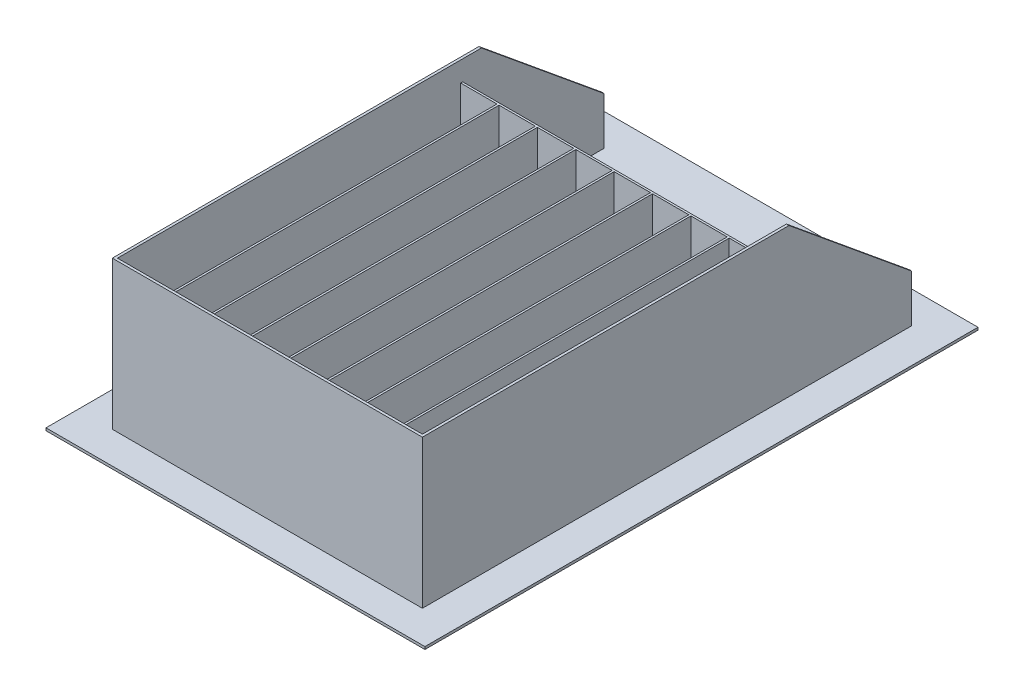
SolidWorks part; units mm, degrees
material "6061-T6 (SS)"
ref_plane "Front Plane" through (0, 0, 0) normal (0, 0, 1) x (1, 0, 0)
ref_plane "Top Plane" through (0, 0, 0) normal (0, 1, 0) x (1, 0, 0)
ref_plane "Right Plane" through (0, 0, 0) normal (1, 0, 0) x (0, 0, -1)
sketch "Sketch1" plane through (0, 0, 0) normal (0, 1, 0) x (1, 0, 0)
  line L1 (0, 0) -> (45.6, 0)
  line L2 (0, 0) -> (0, 430.25)
  line L3 (0, 430.25) -> (45.6, 430.25)
  line L4 (382.3, 0) -> (382.3, 430.25)
  line L5 (385.5, -3.2) -> (385.5, 432.75)
  line L6 (-3.2, -3.2) -> (385.5, -3.2)
  line L7 (-3.2, -3.2) -> (-3.2, 432.75)
  line L8 (-3.2, 433.45) -> (385.5, 433.45) construction
  line L9 (-3.2, 432.75) -> (385.5, 432.75)
  line L10 (45.6, 430.25) -> (45.6, 0)
  line L11 (-3.2, -3.2) -> (-3.2, 433.45) construction
  line L12 (385.5, -3.2) -> (385.5, 433.45) construction
  line L13 (48.1, 0) -> (48.1, 430.25)
  line L14 (48.1, 430.25) -> (93.7, 430.25)
  line L15 (48.1, 0) -> (93.7, 0)
  line L16 (0, 430.25) -> (382.3, 430.25) construction
  line L17 (93.7, 430.25) -> (93.7, 0)
  line L18 (0, 0) -> (382.3, 0) construction
  line L19 (96.2, 0) -> (96.2, 430.25)
  line L20 (141.8, 430.25) -> (141.8, 0)
  line L21 (144.3, 0) -> (144.3, 430.25)
  line L22 (189.9, 430.25) -> (189.9, 0)
  line L23 (192.4, 0) -> (192.4, 430.25)
  line L24 (238, 430.25) -> (238, 0)
  line L25 (240.5, 0) -> (240.5, 430.25)
  line L26 (286.1, 430.25) -> (286.1, 0)
  line L27 (288.6, 0) -> (288.6, 430.25)
  line L28 (334.2, 430.25) -> (334.2, 0)
  line L29 (336.7, 0) -> (336.7, 430.25)
  line L30 (96.2, 430.25) -> (141.8, 430.25)
  line L31 (144.3, 430.25) -> (189.9, 430.25)
  line L32 (96.2, 0) -> (141.8, 0)
  line L33 (144.3, 0) -> (189.9, 0)
  line L34 (192.4, 0) -> (238, 0)
  line L35 (240.5, 0) -> (286.1, 0)
  line L36 (288.6, 0) -> (334.2, 0)
  line L37 (336.7, 0) -> (382.3, 0)
  line L38 (192.4, 430.25) -> (238, 430.25)
  line L39 (240.5, 430.25) -> (286.1, 430.25)
  line L40 (288.6, 430.25) -> (334.2, 430.25)
  line L41 (336.7, 430.25) -> (382.3, 430.25)
  dimension "D1" = 430.25
  dimension "D2" = 382.3
  dimension "D4" = 2.5
  dimension "D3" = 3.2
  dimension "D5" = 2.5
  dimension "D6" = 45.6
  dimension "D8" = 45.6
  dimension "D7" = 7
extrude "Boss-Extrude1" add sketch "Sketch1" along normal blind 189
sketch "Sketch2" plane through (0, 0, 3.2) normal (0, 0, 1) x (1, 0, 0)
  line L0 (385.5, 189) -> (385.5, 0) construction
  line L1 (-3.2, 0) -> (385.5, 0)
  line L2 (-3.2, 0) -> (-3.2, 3.2)
  line L3 (-3.2, 3.2) -> (385.5, 3.2)
  line L4 (385.5, 0) -> (385.5, 3.2)
  dimension "D1" = 3.2
extrude "Boss-Extrude2" add sketch "Sketch2" against normal through all
sketch "Sketch3" plane through (0, 189, 0) normal (0, 1, 0) x (1, 0, 0)
  line L0 (0, 430.25) -> (0, 432.75)
  line L1 (385.5, 432.75) -> (-3.2, 432.75) construction
  line L2 (0, 432.75) -> (382.3, 432.75)
  line L3 (382.3, 430.25) -> (382.3, 432.75)
  line L4 (382.3, 430.25) -> (336.7, 430.25)
  line L5 (336.7, 430.25) -> (336.7, 0)
  line L6 (336.7, 0) -> (334.2, 0)
  line L7 (334.2, 0) -> (334.2, 430.25) construction
  line L8 (334.2, 0) -> (334.2, 430.25) construction
  line L9 (334.2, 0) -> (334.2, 430.25)
  line L10 (334.2, 430.25) -> (288.6, 430.25)
  line L11 (288.6, 430.25) -> (288.6, 0)
  line L12 (288.6, 0) -> (286.1, 0)
  line L13 (286.1, 0) -> (286.1, 430.25)
  line L14 (286.1, 430.25) -> (240.5, 430.25)
  line L15 (240.5, 430.25) -> (240.5, 0)
  line L16 (240.5, 0) -> (238, 0)
  line L17 (238, 0) -> (238, 430.25)
  line L18 (238, 430.25) -> (192.4, 430.25)
  line L19 (192.4, 430.25) -> (192.4, 0)
  line L20 (192.4, 0) -> (189.9, 0)
  line L21 (189.9, 0) -> (189.9, 430.25)
  line L22 (189.9, 430.25) -> (144.3, 430.25)
  line L23 (144.3, 430.25) -> (144.3, 0)
  line L24 (144.3, 0) -> (141.8, 0)
  line L25 (141.8, 0) -> (141.8, 430.25)
  line L26 (141.8, 430.25) -> (96.2, 430.25)
  line L27 (96.2, 430.25) -> (96.2, 0)
  line L28 (96.2, 0) -> (93.7, 0)
  line L29 (93.7, 0) -> (93.7, 430.25)
  line L30 (93.7, 430.25) -> (48.1, 430.25)
  line L31 (48.1, 430.25) -> (48.1, 0)
  line L32 (48.1, 0) -> (45.6, 0)
  line L33 (45.6, 0) -> (45.6, 430.25)
  line L34 (45.6, 430.25) -> (0, 430.25)
extrude "Cut-Extrude1" cut sketch "Sketch3" against normal blind 25
sketch "Sketch4" plane through (385.5, 0, 0) normal (1, 0, 0) x (0, 0, -1)
  line L0 (432.75, 189) -> (662.75, 0)
  line L1 (432.75, 0) -> (662.75, 0)
  line L2 (432.75, 0) -> (432.75, 189)
  dimension "D1" = 230
extrude "Boss-Extrude4" add sketch "Sketch4" against normal blind 3.2 contours L0 L1 L2
sketch "Sketch7" plane through (-3.2, 0, 0) normal (-1, 0, 0) x (0, 0, 1)
  line L0 (-432.75, 164) -> (-432.75, 189)
  line L8 (-430.25, 3.2) -> (0, 3.2)
  line L9 (0, 3.2) -> (0, 189)
  line L10 (0, 189) -> (-432.75, 189)
  line L11 (-432.75, 189) -> (-662.75, 0)
  line L12 (-662.75, 0) -> (-432.75, 0)
  line L13 (-432.75, 0) -> (-432.75, 164)
  line L14 (-432.75, 164) -> (-430.25, 164)
  line L15 (-430.25, 164) -> (-430.25, 3.2)
  line L19 (-432.75, 189) -> (-662.75, 0)
  line L20 (-662.75, 0) -> (-432.75, 0)
  line L21 (-432.75, 0) -> (-432.75, 164)
  dimension "D1" = 0
extrude "Boss-Extrude5" add sketch "Sketch7" against normal blind 3.2
sketch "Sketch9" plane through (0, 0, 0) normal (1, 0, 0) x (0, 0, -1)
  line L0 (662.75, 0) -> (658.8558, 3.2)
  line L1 (432.75, 0) -> (662.75, 0)
  line L2 (432.75, 0) -> (432.75, 3.2)
  line L3 (432.75, 3.2) -> (658.8558, 3.2)
  line L5 (432.75, 189) -> (662.75, 0) construction
  line L6 (662.75, 0) -> (432.75, 0) construction
  point P2 (652.75, 0)
  dimension "D1" = 3.2
extrude "Boss-Extrude6" add sketch "Sketch9" along normal up to next
sketch "Sketch11" plane through (385.5, 0, 0) normal (1, 0, 0) x (0, 0, -1)
  line L1 (662.75, 0) -> (610.16, 0)
  line L2 (662.75, 0) -> (662.75, 168.0196)
  line L3 (662.75, 168.0196) -> (610.16, 168.0196)
  line L4 (610.16, 0) -> (610.16, 168.0196)
  dimension "D1" = 52.59
extrude "Cut-Extrude2" cut sketch "Sketch11" against normal up to next
sketch "Sketch12" plane through (385.5, 0, 0) normal (1, 0, 0) x (0, 0, -1)
  line L1 (432.75, 189) -> (610.16, 43.2153) construction
  line L2 (442.2732, 200.5891) -> (619.6832, 54.8044)
  line L3 (456.3764, 189) -> (610.16, 62.63)
  line L4 (432.75, 189) -> (610.16, 43.2153)
  line L5 (432.75, 189) -> (456.3764, 189)
  line L6 (610.16, 43.2153) -> (610.16, 62.63)
  dimension "D1" = 15
extrude "Boss-Extrude7" add sketch "Sketch12" against normal blind 3.2
sketch "Sketch13" plane through (-3.2, 0, 0) normal (-1, 0, 0) x (0, 0, 1)
  line L0 (-610.16, 62.63) -> (-610.16, 3.2) construction
  line L1 (-432.75, 189) -> (-610.16, 43.2153) construction
  line L2 (0, 189) -> (-456.3764, 189) construction
  line L3 (-610.16, 62.63) -> (-456.3764, 189) construction
  line L4 (-610.16, 62.63) -> (-610.16, 43.2153)
  line L5 (-432.75, 189) -> (-610.16, 43.2153)
  line L6 (-432.75, 189) -> (-456.3764, 189)
  line L7 (-610.16, 62.63) -> (-456.3764, 189)
extrude "Boss-Extrude8" add sketch "Sketch13" against normal blind 3.2
sketch "Sketch14" plane through (0, 0, -610.16) normal (0, 0, -1) x (-1, 0, 0)
  line L0 (0, 3.2) -> (3.2, 3.2) construction
  line L1 (3.2, 0) -> (3.2, 62.63) construction
  line L2 (-382.3, 3.2) -> (-385.5, 3.2) construction
  line L3 (-385.5, 62.63) -> (-385.5, 0) construction
  line L5 (-385.5, 3.2) -> (3.2, 3.2)
  line L6 (-385.5, 3.2) -> (-385.5, 0)
  line L7 (-385.5, 0) -> (3.2, 0)
  line L8 (3.2, 3.2) -> (3.2, 0)
extrude "Boss-Extrude9" add sketch "Sketch14" along normal blind 40
sketch "Sketch15" plane through (0, 0, 3.2) normal (0, 0, 1) x (1, 0, 0)
  line L0 (385.5, 189) -> (385.5, 0) construction
  line L1 (-3.2, 0) -> (385.5, 0)
  line L2 (-3.2, 0) -> (-3.2, 3.2)
  line L3 (-3.2, 3.2) -> (385.5, 3.2)
  line L4 (385.5, 0) -> (385.5, 3.2)
  dimension "D1" = 3.2
extrude "Boss-Extrude10" add sketch "Sketch15" along normal blind 40
sketch "Sketch16" plane through (385.5, 0, 0) normal (1, 0, 0) x (0, 0, -1)
  line L1 (-43.2, 3.2) -> (650.16, 3.2)
  line L2 (-43.2, 3.2) -> (-43.2, 0)
  line L3 (-43.2, 0) -> (650.16, 0)
  line L4 (650.16, 3.2) -> (650.16, 0)
extrude "Boss-Extrude11" add sketch "Sketch16" along normal blind 43.15
sketch "Sketch17" plane through (-3.2, 0, 0) normal (-1, 0, 0) x (0, 0, 1)
  line L1 (-650.16, 3.2) -> (43.2, 3.2)
  line L2 (-650.16, 3.2) -> (-650.16, 0)
  line L3 (-650.16, 0) -> (43.2, 0)
  line L4 (43.2, 3.2) -> (43.2, 0)
extrude "Boss-Extrude12" add sketch "Sketch17" along normal blind 43.15
